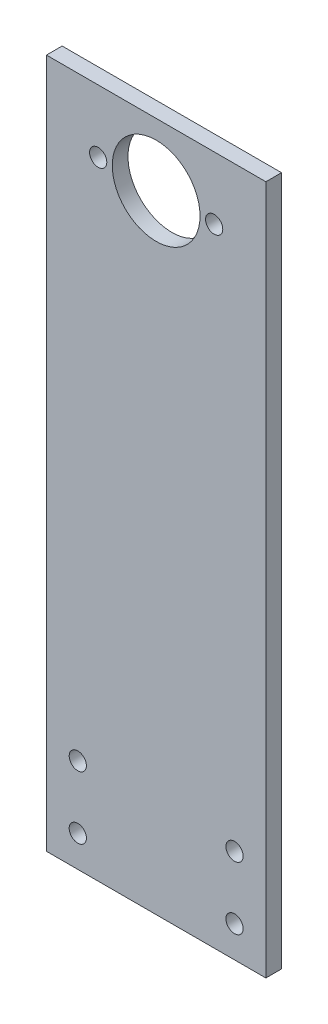
SolidWorks part; units mm, degrees
ref_plane "Front Plane" through (0, 0, 0) normal (0, 0, 1) x (1, 0, 0)
ref_plane "Top Plane" through (0, 0, 0) normal (0, 1, 0) x (1, 0, 0)
ref_plane "Right Plane" through (0, 0, 0) normal (1, 0, 0) x (0, 0, -1)
sketch "Sketch1" plane through (0, 0, 0) normal (0, 0, 1) x (1, 0, 0)
  line L0 (0, 0) -> (0, 100) construction
  line L1 (-35, -100) -> (35, -100) construction
  line L2 (-35, -100) -> (-35, 100)
  line L3 (-35, 100) -> (35, 100)
  line L4 (35, -100) -> (35, 100)
  line L5 (-35, -100) -> (35, 100) construction
  line L6 (-35, 100) -> (35, -100) construction
  line L7 (-18.5, 80) -> (18.5, 80) construction
  line L8 (0, 0) -> (0, -100) construction
  line L9 (-25, -90) -> (25, -90) construction
  line L10 (-35, -100) -> (-35, -120)
  line L11 (56.5225, -120) -> (-643.4775, -120) construction
  line L12 (-35, -120) -> (35, -120)
  line L13 (35, -120) -> (35, -100)
  circle A0 centre (-18.5, 80) radius 2.75
  circle A1 centre (18.5, 80) radius 2.75
  circle A2 centre (0, 80) radius 5
  circle A3 centre (-25, -90) radius 2.75
  circle A4 centre (25, -90) radius 2.75
  circle A5 centre (25, -110) radius 2.75
  circle A6 centre (-25, -110) radius 2.75
  circle A7 centre (0, 80) radius 14
  point P0 (0, 0)
  point P10 (0, 80)
  point P18 (0, -90)
  point P29 (0, 0)
  dimension "D4" = 5.5
  dimension "D5" = 10
  dimension "D6" = 5.5
  dimension "D11" = 28
  dimension "D1" = 70
  dimension "D2" = 200
  dimension "D3" = 37
  dimension "D7" = 10
  dimension "D8" = 20
  dimension "D9" = 10
  dimension "D10" = 20
extrude "Boss-Extrude1" add sketch "Sketch1" along normal blind 5 contours L12 L13 L4 L3 L2 L10 A7 A6 A5 A4 A3 A1 A0
